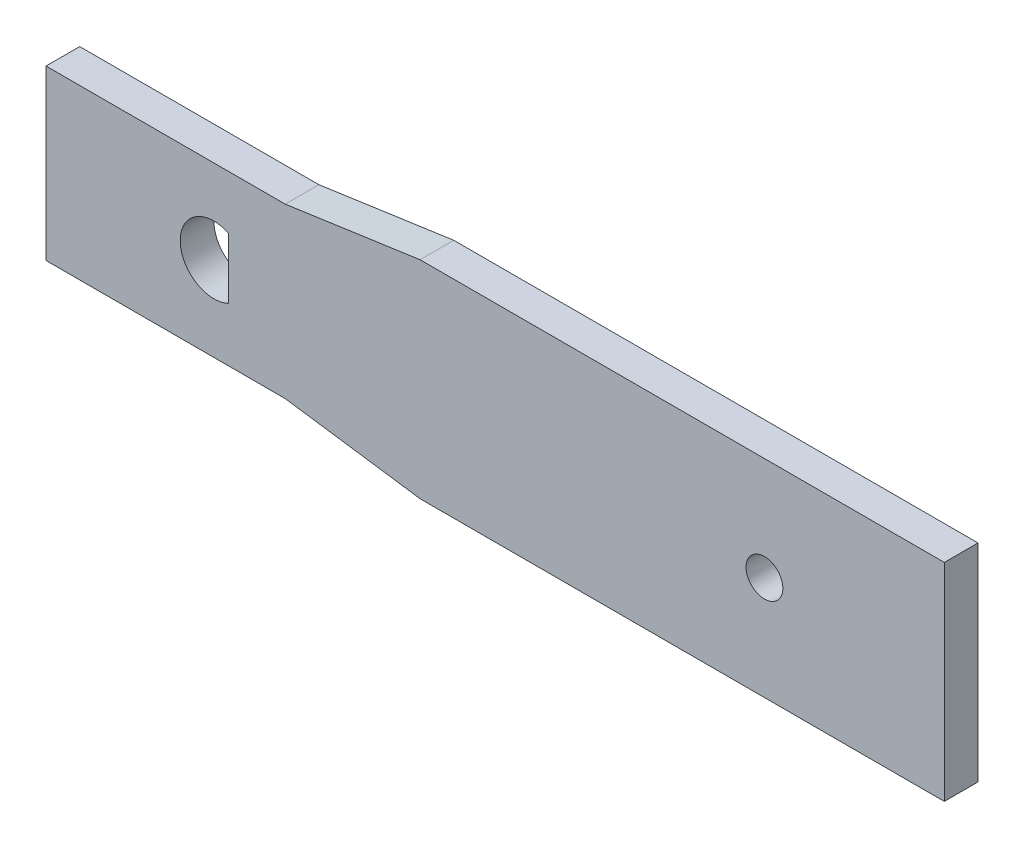
SolidWorks part; units mm, degrees
ref_plane "Front Plane" through (0, 0, 0) normal (0, 0, 1) x (1, 0, 0)
ref_plane "Top Plane" through (0, 0, 0) normal (0, 1, 0) x (1, 0, 0)
ref_plane "Right Plane" through (0, 0, 0) normal (1, 0, 0) x (0, 0, -1)
sketch "Model" plane through (0, 0, 0) normal (0, 0, 1) x (1, 0, 0)
  line L207 (-325.1011, 303.6325) -> (-325.1011, 281.9366)
  line L210 (-398.2841, 298.0765) -> (-364.3981, 303.6325)
  line L211 (-398.2841, 287.6841) -> (-364.0012, 281.9366)
  line L212 (-328.3518, 297.4919) -> (-328.3518, 294.4919)
  line L213 (-328.3518, 294.4919) -> (-333.3048, 294.4919)
  line L214 (-333.3048, 294.4919) -> (-333.3048, 297.4919)
  line L215 (-333.3048, 297.4919) -> (-328.3518, 297.4919)
  line L216 (-356.7454, 297.4919) -> (-356.7454, 294.4919)
  line L217 (-356.7454, 294.4919) -> (-361.6984, 294.4919)
  line L218 (-361.6984, 294.4919) -> (-361.6984, 297.4919)
  line L219 (-361.6984, 297.4919) -> (-356.7454, 297.4919)
  line L220 (-328.3518, 289.1977) -> (-328.3518, 286.1977)
  line L221 (-328.3518, 286.1977) -> (-333.3048, 286.1977)
  line L222 (-333.3048, 286.1977) -> (-333.3048, 289.1977)
  line L223 (-333.3048, 289.1977) -> (-328.3518, 289.1977)
  line L224 (-356.7454, 289.1977) -> (-356.7454, 286.1977)
  line L225 (-356.7454, 286.1977) -> (-361.6984, 286.1977)
  line L226 (-361.6984, 286.1977) -> (-361.6984, 289.1977)
  line L227 (-361.6984, 289.1977) -> (-356.7454, 289.1977)
  line L246 (-399.3267, 292.8803) -> (-399.5986, 292.5257)
  line L247 (-399.5986, 292.5257) -> (-399.496, 292.0923)
  line L248 (-399.496, 292.0923) -> (-399.8901, 291.8778)
  line L249 (-399.8901, 291.8778) -> (-399.9743, 291.4406)
  line L250 (-399.9743, 291.4406) -> (-400.4225, 291.4033)
  line L251 (-400.4225, 291.4033) -> (-400.6792, 291.0378)
  line L252 (-400.6792, 291.0378) -> (-401.1039, 291.1841)
  line L253 (-401.1039, 291.1841) -> (-401.4886, 290.9535)
  line L254 (-401.4886, 290.9535) -> (-401.8166, 291.2582)
  line L255 (-401.8166, 291.2582) -> (-402.2627, 291.2025)
  line L256 (-402.2627, 291.2025) -> (-402.437, 291.6128)
  line L257 (-402.437, 291.6128) -> (-402.8676, 291.7416)
  line L258 (-402.8676, 291.7416) -> (-402.8582, 292.1866)
  line L259 (-402.8582, 292.1866) -> (-403.1986, 292.4775)
  line L260 (-403.1986, 292.4775) -> (-403.0072, 292.8803)
  line L261 (-403.0072, 292.8803) -> (-403.1986, 293.2831)
  line L262 (-403.1986, 293.2831) -> (-402.8582, 293.574)
  line L263 (-402.8582, 293.574) -> (-402.8676, 294.019)
  line L264 (-402.8676, 294.019) -> (-402.437, 294.1478)
  line L265 (-402.437, 294.1478) -> (-402.2627, 294.5581)
  line L266 (-402.2627, 294.5581) -> (-401.8166, 294.5024)
  line L267 (-401.8166, 294.5024) -> (-401.4886, 294.8071)
  line L268 (-401.4886, 294.8071) -> (-401.1039, 294.5765)
  line L269 (-401.1039, 294.5765) -> (-400.6792, 294.7228)
  line L270 (-400.6792, 294.7228) -> (-400.4225, 294.3573)
  line L271 (-400.4225, 294.3573) -> (-399.9743, 294.32)
  line L272 (-399.9743, 294.32) -> (-399.8901, 293.8828)
  line L273 (-399.8901, 293.8828) -> (-399.496, 293.6683)
  line L274 (-399.496, 293.6683) -> (-399.5986, 293.2349)
  line L275 (-399.5986, 293.2349) -> (-399.3267, 292.8803)
  spline S328 degree 3 poles (-398.2841, 298.0765) (-399.1963, 298.6031) (-400.2309, 298.8803) (-401.2841, 298.8803) knots 0 0 0 0 0.2 0.2 0.2 0.2
  spline S329 degree 3 poles (-401.2841, 298.8803) (-404.5978, 298.8803) (-407.284, 296.1941) (-407.284, 292.8803) knots 0.2 0.2 0.2 0.2 0.4 0.4 0.4 0.4
  spline S330 degree 3 poles (-407.284, 292.8803) (-407.284, 289.5665) (-404.5978, 286.8803) (-401.2841, 286.8803) knots 0.4 0.4 0.4 0.4 0.6 0.6 0.6 0.6
  spline S331 degree 3 poles (-401.2841, 286.8803) (-400.2309, 286.8803) (-399.1963, 287.1575) (-398.2841, 287.6841) knots 0.6 0.6 0.6 0.6 1 1 1 1
sketch "Sketch1" plane through (0, 0, 0) normal (0, 0, 1) x (1, 0, 0)
  line L0 (-398.2841, 298.0765) -> (-386.2712, 299.7943)
  line L1 (-386.2712, 299.7943) -> (-339.5874, 299.7943)
  line L2 (-339.5874, 299.7943) -> (-339.5874, 281.3587)
  line L3 (-339.5874, 281.3587) -> (-386.2712, 281.3587)
  line L4 (-386.2712, 281.3587) -> (-398.2841, 283.0765)
  line L5 (-419.5874, 290.5765) -> (-339.5874, 290.5765) construction
  line L23 (-398.2841, 298.0765) -> (-419.5874, 298.0765)
  line L25 (-398.2841, 283.0765) -> (-419.5874, 283.0765)
  line L26 (-419.5874, 298.0765) -> (-419.5874, 283.0765)
  dimension "D3" = 80
  dimension "D2" = 15
extrude "Boss-Extrude1" add sketch "Sketch1" along normal blind 3
sketch "Sketch2" plane through (0, 0, 0) normal (0, 0, -1) x (-1, 0, 0)
  line L0 (419.5874, 298.0765) -> (419.5874, 283.0765) construction
  circle A0 centre (404.6056, 290.5996) radius 3.03
  dimension "D2" = 6.06
  dimension "D1" = 14.9817
sketch "Sketch4" plane through (0, 0, 0) normal (0, 0, -1) x (-1, 0, 0)
  circle A0 centre (355.6056, 290.5996) radius 1.64
  dimension "D1" = 3.28
  dimension "D2" = 49
sketch "Sketch5" plane through (0, 0, 0) normal (0, 0, -1) x (-1, 0, 0)
  line L0 (403.3211, 293.2996) -> (403.3211, 287.8996)
  arc A0 (403.3211, 287.8996) -> (403.3211, 293.2996) centre (404.6336, 290.5996) ccw
extrude "Cut-Extrude3" cut sketch "Sketch5" against normal through all
extrude "Cut-Extrude2" cut sketch "Sketch4" against normal through all
equation "\"selftap\"=1.2"
